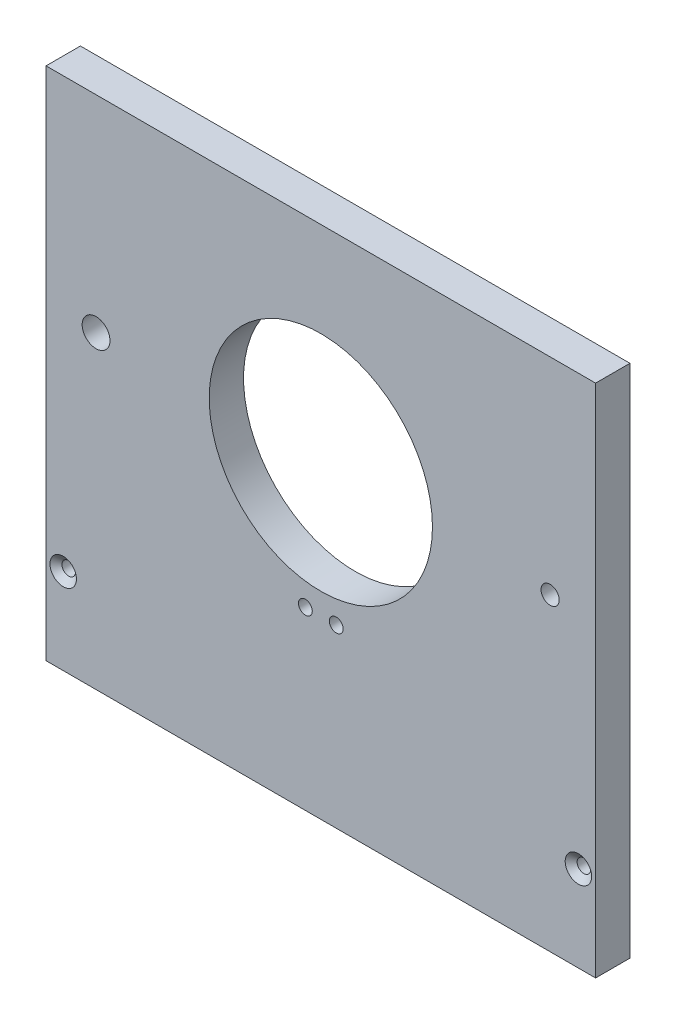
SolidWorks part; units mm, degrees
ref_plane "Front Plane" through (0, 0, 0) normal (0, 0, 1) x (1, 0, 0)
ref_plane "Top Plane" through (0, 0, 0) normal (0, 1, 0) x (1, 0, 0)
ref_plane "Right Plane" through (0, 0, 0) normal (1, 0, 0) x (0, 0, -1)
sketch "Sketch1" plane through (0, 0, 0) normal (0, 0, 1) x (1, 0, 0)
  line L1 (-101.6, -95.25) -> (101.6, -95.25)
  line L2 (-101.6, -95.25) -> (-101.6, 95.25)
  line L3 (-101.6, 95.25) -> (101.6, 95.25)
  line L4 (101.6, -95.25) -> (101.6, 95.25)
  line L5 (-101.6, -95.25) -> (101.6, 95.25) construction
  line L6 (-101.6, 95.25) -> (101.6, -95.25) construction
  point P0 (0, 0)
  dimension "D1" = 203.2
  dimension "D2" = 190.5
extrude "Boss-Extrude1" add sketch "Sketch1" along normal blind 12.7 contours L3 L4 L1 L2
sketch "Sketch2" plane through (0, 0, 12.7) normal (0, 0, 1) x (1, 0, 0)
  line L2 (-101.6, -95.25) -> (101.6, -95.25) construction
  line L3 (-101.6, -95.25) -> (-101.6, 95.25) construction
  circle A0 centre (0, 19.05) radius 41.275
  circle A1 centre (-83.1093, 19.05) radius 5.1435
  circle A2 centre (84.7847, 19.05) radius 3.3655
  dimension "D1" = 10.287
  dimension "D2" = 6.731
  dimension "D5" = 83.1093
  dimension "D6" = 114.3
  dimension "D3" = 82.55
  dimension "D7" = 18.4907
  dimension "D8" = 114.3
  dimension "D9" = 114.3
  dimension "D4" = 167.894
extrude "Cut-Extrude1" cut sketch "Sketch2" against normal through all
hole_wizard "#10-32 Tapped Hole1" positions "Sketch4" profile "Sketch3" tap size "#10-32" standard "ANSI Inch"
sketch "Sketch4" plane through (0, -95.25, 0) normal (0, -1, 0) x (-1, 0, 0)
  line L0 (101.6, -12.7) -> (101.6, 0) construction
  line L1 (101.6, -12.7) -> (-101.6, -12.7) construction
  line L2 (-101.6, -12.7) -> (-101.6, 0) construction
  point P0 (82.55, -6.35)
  point P2 (0, -6.35)
  point P4 (-82.55, -6.35)
  point P9 (0, -12.7)
  dimension "D1" = 19.05
  dimension "D2" = 0
  dimension "D3" = 19.05
sketch "Sketch3" plane through (-82.55, -95.25, 6.35) normal (1, 0, 0) x (0, 0, -1)
  line L0 (0, 0) -> (0, 26.6133)
  line L1 (0, 26.6133) -> (2.0193, 25.4)
  line L2 (2.0193, 25.4) -> (2.0193, 0)
  line L5 (2.0193, 0) -> (0, 0)
  line L10 (0, 26.6133) -> (-2.0193, 25.4) construction
  line L11 (0, -6.35) -> (0, 107.95) construction
  dimension "Tap Drill Dia." = 4.0386
  dimension "Tap Drill Depth" = 25.4
  dimension "Drill Angle" = 118
hole_wizard "CSK for #10 Flat Head Machine Screw (100)1" positions "Sketch6" profile "Sketch5" countersink size "#10" standard "ANSI Inch" end condition through all
sketch "Sketch6" plane through (0, 0, 12.7) normal (0, 0, 1) x (1, 0, 0)
  line L0 (-101.6, -95.25) -> (101.6, -95.25) construction
  line L1 (-101.6, -95.25) -> (-101.6, 95.25) construction
  line L2 (101.6, -95.25) -> (101.6, 95.25) construction
  point P0 (-95.25, -63.5)
  point P7 (95.25, -63.5)
  dimension "D1" = 31.75
  dimension "D2" = 6.35
  dimension "D3" = 31.75
  dimension "D4" = 6.35
sketch "Sketch5" plane through (-95.25, -63.5, 12.7) normal (1, 0, 0) x (0, -1, 0)
  line L0 (0, 0) -> (0, 12.7)
  line L1 (0, 12.7) -> (2.4892, 12.7)
  line L2 (2.4892, 12.7) -> (2.4892, 2.0141)
  line L3 (2.4892, 2.0141) -> (4.8895, 0)
  line L5 (4.8895, 0) -> (0, 0)
  line L6 (-2.4892, 2.0141) -> (-4.8895, 0) construction
  line L11 (0, -6.35) -> (0, 107.95) construction
  dimension "Thru Hole Dia." = 4.9784
  dimension "Thru Hole Depth" = 12.7
  dimension "Near C'Sink Dia." = 9.779
  dimension "Near C'Sink Angle" = 100
hole_wizard "#7 (0.201) Diameter Hole1" positions "Sketch8" profile "Sketch7" hole size "#7" standard "ANSI Inch" end condition through all
sketch "Sketch8" plane through (0, 0, 12.7) normal (0, 0, 1) x (1, 0, 0)
  line L0 (-101.6, 95.25) -> (101.6, 95.25) construction
  line L1 (-101.6, -95.25) -> (-101.6, 95.25) construction
  point P0 (-5.715, -30.1625)
  point P2 (5.715, -30.1625)
  dimension "D1" = 125.4125
  dimension "D2" = 0
  dimension "D3" = 95.885
  dimension "D4" = 11.43
sketch "Sketch7" plane through (-5.715, -30.1625, 12.7) normal (1, 0, 0) x (0, -1, 0)
  line L0 (0, 0) -> (0, 12.7)
  line L1 (0, 12.7) -> (2.5527, 12.7)
  line L2 (2.5527, 12.7) -> (2.5527, 0)
  line L5 (2.5527, 0) -> (0, 0)
  line L11 (0, -6.35) -> (0, 107.95) construction
  dimension "Thru Hole Dia." = 5.1054
  dimension "Thru Hole Depth" = 12.7
